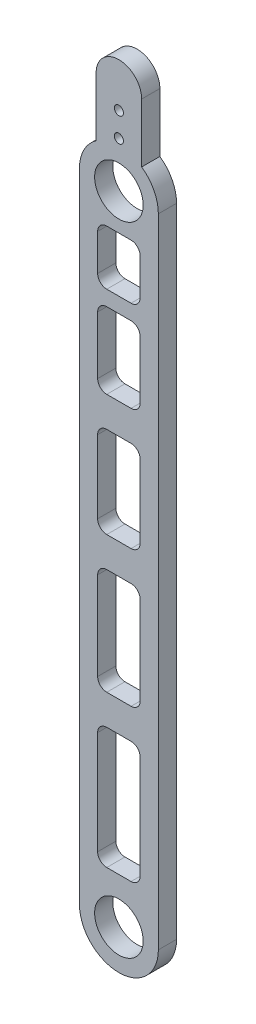
SolidWorks part; units mm, degrees
material "6061 合金"
ref_plane "前视基准面" through (0, 0, 0) normal (0, 0, 1) x (1, 0, 0)
ref_plane "上视基准面" through (0, 0, 0) normal (0, 1, 0) x (1, 0, 0)
ref_plane "右视基准面" through (0, 0, 0) normal (1, 0, 0) x (0, 0, -1)
sketch "草图1" plane through (0, 0, 0) normal (0, 0, 1) x (1, 0, 0)
  line L0 (0, 279.0477) -> (0, -66.8302) construction
  line L1 (-89.617, 0) -> (101.5542, 0) construction
  line L2 (-13, 0) -> (-13, 210)
  line L3 (13, 0) -> (13, 210)
  line L5 (-7.5, 240) -> (7.5, 240) construction
  line L6 (-7.5, 240) -> (-7.5, 220.6184)
  line L7 (-5.0299, 220.6184) -> (7.5, 220.6184) construction
  line L8 (7.5, 240) -> (7.5, 220.6184)
  circle A0 centre (0, 0) radius 8
  circle A1 centre (0, 210) radius 8
  arc A2 (-13, 0) -> (13, 0) centre (0, 0) ccw
  circle A3 centre (0, 210) radius 13 construction
  arc A4 (7.5, 240) -> (-7.5, 240) centre (0, 240) ccw
  arc A5 (-13, 210) -> (-7.5, 220.6184) centre (0, 210) cw
  arc A6 (7.5, 220.6184) -> (13, 210) centre (0, 210) cw
  point P14 (13, 0)
  point P21 (13, 200)
  point P22 (-13, 200)
  point P23 (0, 0)
  point P24 (-5.0299, 211.9875)
  dimension "D1" = 16
  dimension "D2" = 210
  dimension "D3" = 16
  dimension "D4" = 5
  dimension "D5" = 5
  dimension "D6" = 15
  dimension "D7" = 30
extrude "凸台-拉伸1" add sketch "草图1" along normal blind 6
sketch "草图2" plane through (0, 0, 6) normal (0, 0, 1) x (1, 0, 0)
  line L0 (0, 0) -> (0, 269.7507) construction
  line L1 (13, 0) -> (13, 210) construction
  line L2 (-7, 175) -> (7, 175)
  line L3 (-7, 175) -> (-7, 150)
  line L4 (-7, 150) -> (7, 150)
  line L5 (7, 175) -> (7, 150)
  line L6 (-7, 175) -> (7, 150) construction
  line L7 (-7, 150) -> (7, 175) construction
  line L8 (-7, 140) -> (7, 140)
  line L9 (-7, 140) -> (-7, 110)
  line L10 (-7, 110) -> (7, 110)
  line L11 (7, 140) -> (7, 110)
  line L12 (-7, 140) -> (7, 110) construction
  line L13 (-7, 110) -> (7, 140) construction
  line L14 (-7, 100) -> (7, 100)
  line L15 (-7, 100) -> (-7, 65)
  line L16 (-7, 65) -> (7, 65)
  line L17 (7, 100) -> (7, 65)
  line L18 (-7, 100) -> (7, 65) construction
  line L19 (-7, 65) -> (7, 100) construction
  line L20 (-7, 55) -> (7, 55)
  line L21 (-7, 55) -> (-7, 15)
  line L22 (-7, 15) -> (7, 15)
  line L23 (7, 55) -> (7, 15)
  line L24 (-7, 55) -> (7, 15) construction
  line L25 (-7, 15) -> (7, 55) construction
  line L27 (-7, 198) -> (7, 198)
  line L28 (-7, 198) -> (-7, 180)
  line L29 (-7, 180) -> (7, 180)
  line L30 (7, 198) -> (7, 180)
  line L31 (-7, 198) -> (7, 180) construction
  line L32 (-7, 180) -> (7, 198) construction
  circle A0 centre (0, 0) radius 8 construction
  circle A1 centre (0, 210) radius 8 construction
  circle A2 centre (0, 233) radius 1.5
  circle A3 centre (0, 225) radius 1.5
  point P3 (0, 162.5)
  point P8 (0, 125)
  point P13 (0, 82.5)
  point P18 (0, 35)
  point P32 (0, 189)
  dimension "D12" = 3
  dimension "D13" = 8
  dimension "D14" = 15
  dimension "D1" = 6
  dimension "D2" = 15
  dimension "D3" = 40
  dimension "D4" = 10
  dimension "D5" = 35
  dimension "D6" = 10
  dimension "D7" = 30
  dimension "D8" = 10
  dimension "D9" = 25
  dimension "D10" = 5
  dimension "D11" = 12
extrude "切除-拉伸1" cut sketch "草图2" against normal through all
fillet "圆角1" radius 3 20 edges at (7, 198, 3) (-7, 198, 3) (7, 180, 3) (-7, 180, 3) (-7, 175, 3) (7, 175, 3) (7, 150, 3) (-7, 150, 3) (-7, 140, 3) (7, 140, 3) (7, 110, 3) (-7, 110, 3) (7, 100, 3) (-7, 100, 3) (7, 65, 3) (-7, 65, 3) (7, 15, 3) (-7, 15, 3) (-7, 55, 3) (7, 55, 3)
